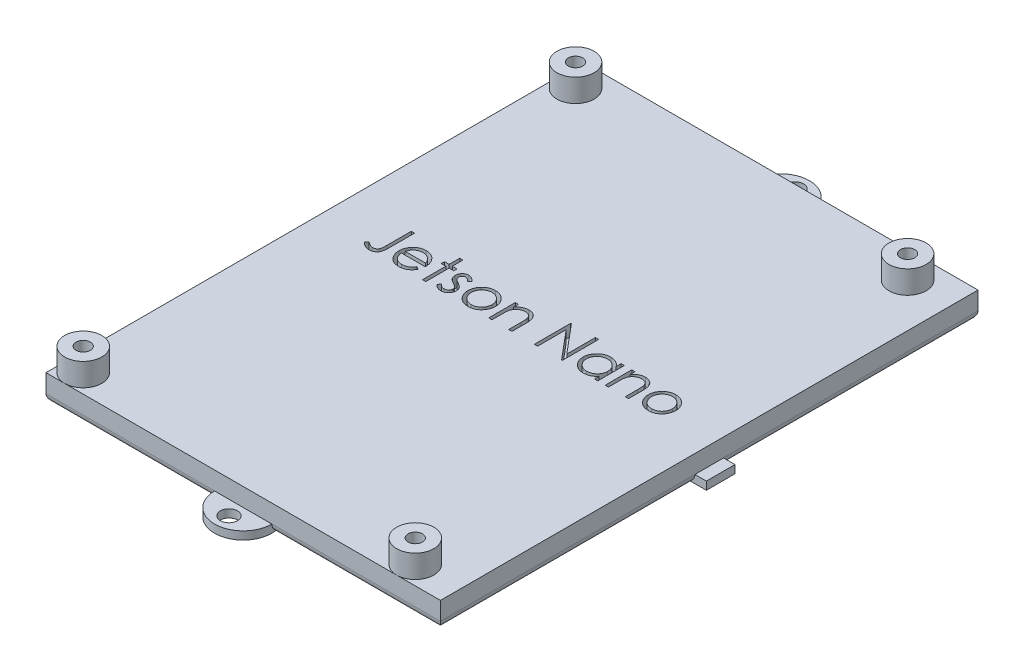
SolidWorks part; units mm, degrees
ref_plane "Front Plane" through (0, 0, 0) normal (0, 0, 1) x (1, 0, 0)
ref_plane "Top Plane" through (0, 0, 0) normal (0, 1, 0) x (1, 0, 0)
ref_plane "Right Plane" through (0, 0, 0) normal (1, 0, 0) x (0, 0, -1)
sketch "Sketch1" plane through (0, 0, 0) normal (0, 1, 0) x (1, 0, 0)
  line L0 (-34.45, 46.95) -> (34.45, 46.95)
  line L5 (-34.45, 46.95) -> (-34.45, -46.95)
  line L6 (-34.45, -46.95) -> (34.45, -46.95)
  line L7 (34.45, 46.95) -> (34.45, -46.95)
  point P11 (-34.45, 0)
  point P12 (0, -46.95)
  dimension "D3" = 93.9
  dimension "D4" = 68.9
extrude "Boss-Extrude1" add sketch "Sketch1" along normal blind 4.575
sketch "Sketch8" plane through (0, 4.575, 0) normal (0, 1, 0) x (1, 0, 0)
  line L0 (-34.45, -46.95) -> (34.45, -46.95) construction
  line L1 (-34.45, 46.95) -> (-34.45, -46.95) construction
  circle A0 centre (-31.2, -43.7) radius 1.25
  circle A1 centre (-31.2, 42.3) radius 1.25
  circle A2 centre (26.8, 42.3) radius 1.25
  circle A3 centre (26.8, -43.7) radius 1.25
  circle A4 centre (-31.2, 42.3) radius 3.25
  circle A5 centre (26.8, 42.3) radius 3.25
  circle A6 centre (26.8, -43.7) radius 3.25
  circle A7 centre (-31.2, -43.7) radius 3.25
  dimension "D3" = 2.5
  dimension "D4" = 2
  dimension "D1" = 58
  dimension "D2" = 86
extrude "Boss-Extrude5" add sketch "Sketch8" along normal blind 4
sketch "Sketch3" plane through (0, 4.575, 0) normal (0, 1, 0) x (1, 0, 0)
  circle A5 centre (-31.2, -43.7) radius 1.25 construction
  circle A6 centre (-31.2, 42.3) radius 1.25
  circle A7 centre (26.8, 42.3) radius 1.25
  circle A8 centre (26.8, -43.7) radius 1.25
  circle A9 centre (-31.2, -43.7) radius 1.25
  point P8 (-27.45, -41.275)
  point P11 (0, 0)
  point P12 (26.8, -43.7)
  point P13 (-31.2, -43.7)
  point P14 (0, 0)
  point P15 (26.8, 42.3)
  point P23 (0, 0)
  point P24 (-31.2, 42.3)
extrude "Cut-Extrude1" cut sketch "Sketch3" against normal offset from surface (3.575 mm away) 1 up to face at (0, 0, 0)
sketch "Sketch4" plane through (0, 0, 0) normal (0, 1, 0) x (1, 0, 0)
  line L0 (-5, -46.95) -> (5, -46.95)
  line L3 (-34.45, -46.95) -> (34.45, -46.95) construction
  line L4 (0, -46.95) -> (0, -51.95) construction
  arc A0 (-5, -46.95) -> (5, -46.95) centre (0, -46.95) ccw
  circle A2 centre (0, -49.45) radius 1.5
  point P6 (0, -46.95)
  dimension "D2" = 3
  dimension "D3" = 5
extrude "Boss-Extrude3" add sketch "Sketch4" along normal blind 1.4
mirror "Mirror1" about plane through (0, 0, 0) normal (0, 0, 1) of "Boss-Extrude3"
sketch "Sketch5" plane through (0, 4.575, 0) normal (0, 1, 0) x (1, 0, 0)
  line L0 (-30, 0) -> (30, 0) construction
  text T0 "Jetson Nano" font "Century Gothic" height in points 24
  point P6 (0, 0)
  dimension "D1" = 60
extrude "Cut-Extrude2" cut sketch "Sketch5" against normal blind 2
sketch "Sketch6" plane through (-34.45, 0, 0) normal (-1, 0, 0) x (0, 0, 1)
  line L0 (-46.95, 0) -> (46.95, 0) construction
  line L1 (-2.5, 0) -> (2.5, 0)
  line L2 (-2.5, 0) -> (-2.5, 1.4)
  line L3 (-2.5, 1.4) -> (2.5, 1.4)
  line L4 (2.5, 0) -> (2.5, 1.4)
  line L5 (51.95, 1.4) -> (46.95, 1.4) construction
  point P6 (0, 0)
  point P7 (0, 1.4)
  dimension "D1" = 5
extrude "Boss-Extrude4" add sketch "Sketch6" along normal blind 2
mirror "Mirror2" about plane through (0, 0, 0) normal (1, 0, 0) of "Boss-Extrude4"
fillet "Fillet1" radius 1.4 8 edges at (-19.725, 0, 46.95) (19.725, 0, 46.95) (34.45, 0, -24.725) (34.45, 0, 24.725) (19.725, 0, -46.95) (-19.725, 0, -46.95) (-34.45, 0, 24.725) (-34.45, 0, -24.725)
